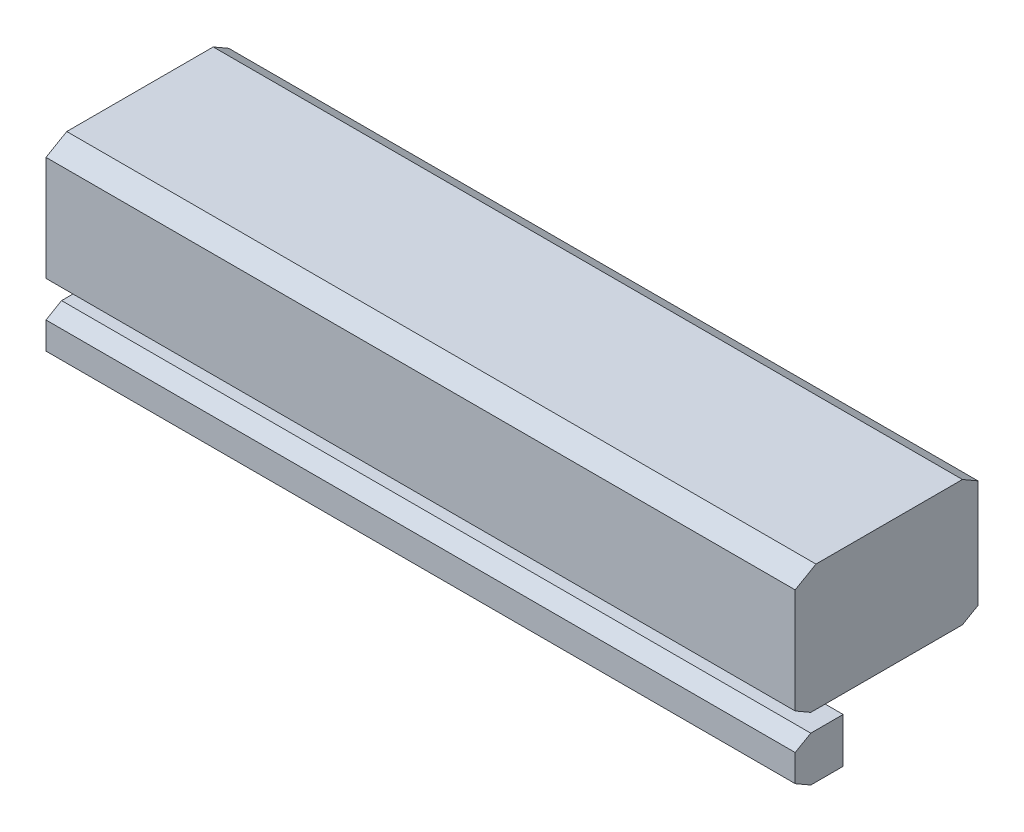
SolidWorks part; units mm, degrees
ref_plane "前视基准面" through (0, 0, 0) normal (0, 0, 1) x (1, 0, 0)
ref_plane "上视基准面" through (0, 0, 0) normal (0, 1, 0) x (1, 0, 0)
ref_plane "右视基准面" through (0, 0, 0) normal (1, 0, 0) x (0, 0, -1)
sketch "草图1" plane through (0, 0, 0) normal (1, 0, 0) x (0, 0, -1)
  line L0 (-61.2293, 0) -> (62.1466, 0) construction
  line L1 (0, 68.9117) -> (0, -64.0959) construction
  line L3 (-30.5, -21) -> (30.5, -21)
  line L4 (-30.5, -21) -> (-30.5, 21)
  line L5 (-30.5, 21) -> (30.5, 21)
  line L6 (30.5, -21) -> (30.5, 21)
  point P9 (0, 21)
  point P10 (30.5, 0)
  dimension "D1" = 61
  dimension "D2" = 42
extrude "凸台-拉伸1" add sketch "草图1" along normal mid plane 250
chamfer "倒角1" distance 4 angle 60 1 edges at (0, 21, 30.5)
chamfer "倒角2" distance 3 angle 60 3 edges at (0, 21, -30.5) (0, -21, -30.5) (0, -21, 30.5)
sketch "草图3" plane through (0, 0, 0) normal (1, 0, 0) x (0, 0, -1)
  line L0 (-25.3038, -21) -> (25.3038, -21) construction
  line L1 (-20.3038, -21) -> (-14.3038, -21)
  line L2 (-20.3038, -21) -> (-20.3038, -42)
  line L3 (-20.3038, -42) -> (-14.3038, -42)
  line L4 (-14.3038, -21) -> (-14.3038, -36)
  line L6 (-14.3038, -42) -> (60.6962, -42)
  line L8 (-14.3038, -36) -> (60.6962, -36)
  line L9 (60.6962, -42) -> (60.6962, -36)
  dimension "D1" = 5
  dimension "D2" = 6
  dimension "D3" = 21
  dimension "D4" = 75
  dimension "D5" = 6
  dimension "D6" = 15
extrude "凸台-拉伸2" add sketch "草图3" along normal mid plane 110
sketch "草图4" plane through (0, 0, 0) normal (1, 0, 0) x (0, 0, -1)
  line L0 (-20.3038, -42) -> (60.6962, -42) construction
  line L1 (-30.5, -42) -> (-14.5, -42)
  line L2 (-30.5, -42) -> (-30.5, -27)
  line L3 (-30.5, -27) -> (-14.5, -27)
  line L4 (-14.5, -42) -> (-14.5, -27)
  line L6 (-30.5, 17) -> (-30.5, -18) construction
  dimension "D1" = 16
  dimension "D2" = 15
extrude "凸台-拉伸3" add sketch "草图4" along normal mid plane 250
chamfer "倒角3" distance 3 angle 60 2 edges at (0, -42, 30.5) (0, -27, 30.5)
sketch "草图5" plane through (0, -42, 0) normal (0, -1, 0) x (1, 0, 0)
  line L0 (55, -60.6962) -> (-55, -60.6962) construction
  line L1 (-35, -50.6962) -> (35, -50.6962)
  line L2 (-35, -50.6962) -> (-35, -17.6962)
  line L3 (-35, -17.6962) -> (35, -17.6962)
  line L4 (35, -50.6962) -> (35, -17.6962)
  line L5 (-55, 14.5) -> (-55, -60.6962) construction
  dimension "D1" = 70
  dimension "D2" = 33
  dimension "D3" = 10
  dimension "D4" = 20
extrude "切除-拉伸1" cut sketch "草图5" against normal up to next
sketch "草图8" plane through (0, -42, 0) normal (0, -1, 0) x (1, 0, 0)
  line L0 (-60.7954, -1.5) -> (68.998, -1.5) construction
  line L1 (0, 39.5534) -> (0, -34.9367) construction
  line L2 (-125, 30.5) -> (125, 30.5) construction
  point P7 (0, -1.5)
  dimension "D1" = 32
hole_wizard "M5 螺纹孔1" positions "草图8" profile "草图9" tap size "M5" standard "ISO"
sketch "草图9" plane through (0, -42, -1.5) normal (1, 0, 0) x (0, 0, -1)
  line L0 (0, 0) -> (0, 6)
  line L1 (0, 6) -> (2.1, 6)
  line L2 (2.1, 6) -> (2.1, 0.425)
  line L3 (2.1, 0.425) -> (2.525, 0)
  line L5 (2.525, 0) -> (0, 0)
  line L6 (-2.1, 0.425) -> (-2.525, 0) construction
  line L11 (0, -6.35) -> (0, 107.95) construction
  dimension "通孔螺纹孔钻头直径" = 4.2
  dimension "通孔螺纹孔钻头深度" = 6
  dimension "近端锥形沉头孔直径" = 5.05
  dimension "近端锥形沉头孔角度" = 90
cosmetic thread "孔螺蚊线1" parameters "D2"=5
